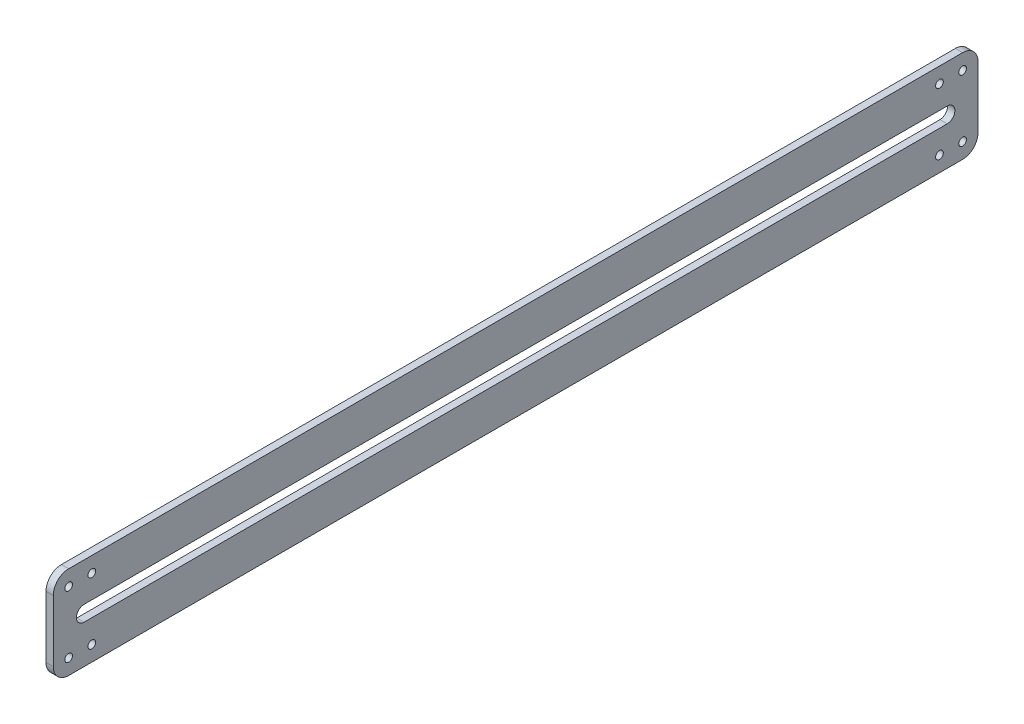
SolidWorks part; units mm, degrees
ref_plane "Front Plane" through (0, 0, 0) normal (0, 0, 1) x (1, 0, 0)
ref_plane "Top Plane" through (0, 0, 0) normal (0, 1, 0) x (1, 0, 0)
ref_plane "Right Plane" through (0, 0, 0) normal (1, 0, 0) x (0, 0, -1)
sketch "Sketch1" plane through (0, 0, 0) normal (1, 0, 0) x (0, 0, -1)
  line L1 (-184.15, -19.05) -> (184.15, -19.05)
  line L2 (-190.5, -12.7) -> (-190.5, 12.7)
  line L3 (-184.15, 19.05) -> (184.15, 19.05)
  line L4 (190.5, -12.7) -> (190.5, 12.7)
  line L5 (-190.5, -19.05) -> (190.5, 19.05) construction
  line L6 (-190.5, 19.05) -> (190.5, -19.05) construction
  arc A0 (184.15, 19.05) -> (190.5, 12.7) centre (184.15, 12.7) cw
  arc A1 (190.5, -12.7) -> (184.15, -19.05) centre (184.15, -12.7) cw
  arc A2 (-184.15, -19.05) -> (-190.5, -12.7) centre (-184.15, -12.7) cw
  arc A3 (-190.5, 12.7) -> (-184.15, 19.05) centre (-184.15, 12.7) cw
  point P0 (0, 0)
  dimension "D3" = 6.35
  dimension "D1" = 381
  dimension "D2" = 38.1
extrude "Outer Cut" add sketch "Sketch1" along normal mid plane 2.9972
sketch "Sketch2" plane through (1.4986, 0, 0) normal (1, 0, 0) x (0, 0, -1)
  line L0 (-190.5, 0) -> (190.5, 0) construction
  line L1 (-190.5, 12.7) -> (-190.5, -12.7) construction
  line L2 (190.5, -12.7) -> (190.5, 12.7) construction
  line L3 (-177.8, 0) -> (177.8, 0) construction
  line L4 (-177.8, 3.175) -> (177.8, 3.175)
  line L5 (-177.8, -3.175) -> (177.8, -3.175)
  arc A0 (-177.8, 3.175) -> (-177.8, -3.175) centre (-177.8, 0) ccw
  arc A1 (177.8, -3.175) -> (177.8, 3.175) centre (177.8, 0) ccw
  point P2 (0, 0)
  dimension "D1" = 6.35
  dimension "D3" = 12.7
  dimension "D4" = 12.7
extrude "Slots" cut sketch "Sketch2" against normal through all
sketch "Sketch3" plane through (1.4986, 0, 0) normal (1, 0, 0) x (0, 0, -1)
  line L0 (-190.5, 12.7) -> (-190.5, -12.7) construction
  line L1 (184.15, 19.05) -> (-184.15, 19.05) construction
  line L2 (0, 0) -> (0, 19.05) construction
  line L3 (0, 0) -> (-190.5, 0) construction
  circle A0 centre (-184.15, 12.7) radius 1.5875
  circle A1 centre (-174.625, 12.7) radius 1.5875
  circle A2 centre (-174.625, -12.7) radius 1.5875
  circle A3 centre (-184.15, -12.7) radius 1.5875
  circle A4 centre (174.625, 12.7) radius 1.5875
  circle A5 centre (184.15, 12.7) radius 1.5875
  circle A6 centre (184.15, -12.7) radius 1.5875
  circle A7 centre (174.625, -12.7) radius 1.5875
  dimension "D1" = 3.175
  dimension "D2" = 6.35
  dimension "D3" = 6.35
  dimension "D5" = 9.525
  dimension "D4" = 2
extrude "Mount Holes" cut sketch "Sketch3" against normal through all
